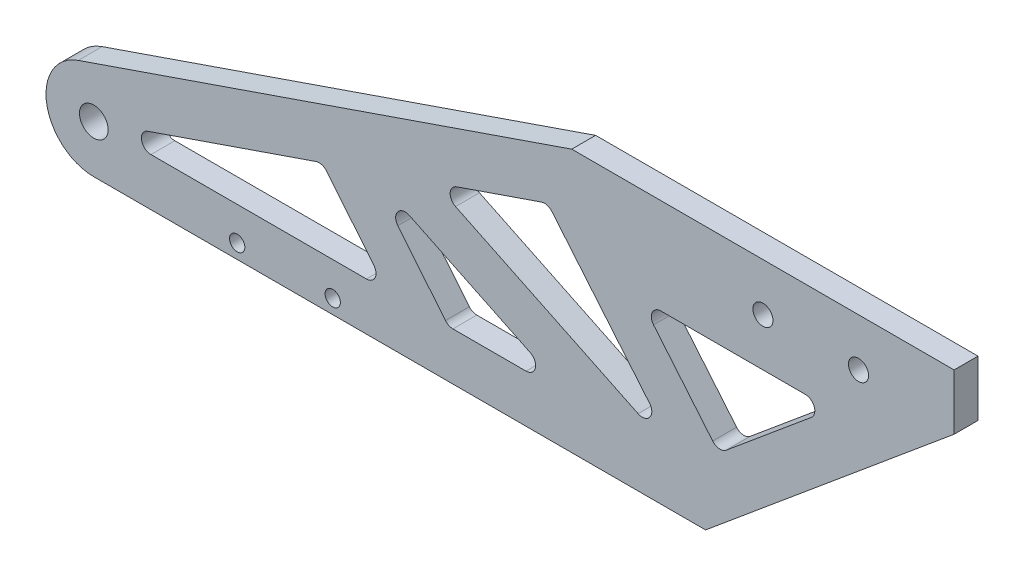
SolidWorks part; units mm, degrees
material "环氧树脂FR-4"
ref_plane "前视基准面" through (0, 0, 0) normal (0, 0, 1) x (1, 0, 0)
ref_plane "上视基准面" through (0, 0, 0) normal (0, 1, 0) x (1, 0, 0)
ref_plane "右视基准面" through (0, 0, 0) normal (1, 0, 0) x (0, 0, -1)
sketch "草图1" plane through (0, 0, 0) normal (0, 0, 1) x (1, 0, 0)
  line L0 (0, 0) -> (0, 55)
  line L1 (0, 55) -> (-80, 55)
  line L3 (-180, 0) -> (0, 0)
  line L4 (-80, 55) -> (-183.2549, 19.4554)
  arc A0 (-183.2549, 19.4554) -> (-180, 0) centre (-180, 10) ccw
  dimension "D4" = 20
  dimension "D1" = 55
  dimension "D2" = 80
  dimension "D3" = 180
  dimension "D6" = 0
extrude "凸台-拉伸1" add sketch "草图1" along normal blind 5
sketch "草图2" plane through (0, 0, 5) normal (0, 0, 1) x (1, 0, 0)
  circle A0 centre (-180, 10) radius 3
  dimension "D1" = 6
extrude "切除-拉伸1" cut sketch "草图2" against normal through all
sketch "草图3" plane through (0, 0, 5) normal (0, 0, 1) x (1, 0, 0)
  line L1 (-80, 55) -> (-183.2549, 19.4554) construction
  line L6 (-113.975, 26.0008) -> (-88.6926, 13.8013)
  line L7 (-89.5618, 10) -> (-104.8668, 10)
  line L17 (-106.415, 10.7338) -> (-116.3924, 22.9334)
  line L26 (-168.6966, 13.8911) -> (-133.51, 26.0037)
  line L30 (-131.3109, 25.3788) -> (-121.4046, 13.2662)
  line L34 (-10, 30.7299) -> (-10, 12)
  line L35 (-12, 10) -> (-34.4759, 10)
  line L36 (-35.7563, 13.5364) -> (-13.2804, 32.2664)
  line L37 (-180, 0) -> (0, 0) construction
  line L38 (0, 0) -> (0, 55) construction
  line L39 (0, 55) -> (-80, 55) construction
  line L40 (-61.3504, 35) -> (-31.1446, 35)
  line L41 (-29.8642, 31.4636) -> (-47.6906, 16.6082)
  line L42 (-50.5074, 16.8643) -> (-62.8869, 31.7196)
  line L43 (-84.1609, 41.628) -> (-63.7173, 17.0956)
  line L44 (-66.1229, 14.014) -> (-104.3075, 32.4392)
  line L45 (-104.0893, 36.1316) -> (-86.3483, 42.2387)
  line L46 (-122.9527, 10) -> (-168.0456, 10)
  arc A0 (-168.6966, 13.8911) -> (-168.0456, 10) centre (-168.0456, 12) ccw
  arc A1 (-10, 12) -> (-12, 10) centre (-12, 12) cw
  arc A2 (-10, 30.7299) -> (-13.2804, 32.2664) centre (-12, 30.7299) ccw
  arc A3 (-34.4759, 10) -> (-35.7563, 13.5364) centre (-34.4759, 12) cw
  arc A4 (-31.1446, 35) -> (-29.8642, 31.4636) centre (-31.1446, 33) cw
  arc A5 (-47.6906, 16.6082) -> (-50.5074, 16.8643) centre (-48.971, 18.1447) cw
  arc A6 (-61.3504, 35) -> (-62.8869, 31.7196) centre (-61.3504, 33) ccw
  arc A7 (-63.7173, 17.0956) -> (-66.1229, 14.014) centre (-65.2537, 15.8153) cw
  arc A8 (-84.1609, 41.628) -> (-86.3483, 42.2387) centre (-85.6974, 40.3476) ccw
  arc A9 (-104.3075, 32.4392) -> (-104.0893, 36.1316) centre (-103.4383, 34.2405) cw
  arc A10 (-88.6926, 13.8013) -> (-89.5618, 10) centre (-89.5618, 12) cw
  arc A11 (-104.8668, 10) -> (-106.415, 10.7338) centre (-104.8668, 12) cw
  arc A12 (-113.975, 26.0008) -> (-116.3924, 22.9334) centre (-114.8442, 24.1995) ccw
  arc A13 (-121.4046, 13.2662) -> (-122.9527, 10) centre (-122.9527, 12) cw
  arc A14 (-133.51, 26.0037) -> (-131.3109, 25.3788) centre (-132.859, 24.1127) cw
  point P27 (-10, 10)
  point P30 (-10, 35)
  point P33 (-40, 10)
  point P36 (-25.6205, 35)
  point P41 (-65.6205, 35)
  point P44 (-57.8042, 10)
  point P47 (-85.044, 42.6877)
  point P50 (-108.6826, 34.5504)
  point P53 (-80.8149, 10)
  point P56 (-105.8149, 10)
  point P59 (-122.1123, 29.9273)
  dimension "D17" = 10
  dimension "D18" = 10
  dimension "D19" = 2
  dimension "D20" = 2
  dimension "D1" = 10
  dimension "D2" = 10
  dimension "D3" = 20
  dimension "D4" = 30
  dimension "D5" = 20
  dimension "D6" = 10
  dimension "D7" = 40
  dimension "D8" = 10
  dimension "D9" = 10
  dimension "D10" = 0
  dimension "D11" = 25
  dimension "D12" = 10
  dimension "D13" = 10
  dimension "D14" = 10
  dimension "D15" = 25
  dimension "D16" = 10
extrude "切除-拉伸2" cut sketch "草图3" against normal through all
sketch "草图4" plane through (0, 0, 5) normal (0, 0, 1) x (1, 0, 0)
  line L0 (-180, 0) -> (0, 0) construction
  circle A0 centre (-180, 10) radius 3 construction
  point P0 (-150, 3)
  point P1 (-130, 3)
  dimension "D1" = 30
  dimension "D2" = 20
  dimension "D3" = 3
  dimension "D4" = 3
hole_wizard "Ø3.2 (3.2) 直径孔1" positions "3D草图1" profile "草图5" hole size "Ø3.2" standard "GB" end condition through all
sketch3d "3D草图1"
  point P0 (-150, 3, 5)
  point P3 (-130, 3, 5)
sketch "草图5" plane through (-150, 3, 5) normal (1, 0, 0) x (0, -1, 0)
  line L0 (0, 0) -> (0, 5)
  line L1 (0, 5) -> (1.6, 5)
  line L2 (1.6, 5) -> (1.6, 0)
  line L5 (1.6, 0) -> (0, 0)
  line L11 (0, -6.35) -> (0, 107.95) construction
  dimension "通孔孔直径" = 3.2
  dimension "通孔孔深度" = 5
sketch "草图6" plane through (0, 0, 5) normal (0, 0, 1) x (1, 0, 0)
  line L0 (0, 55) -> (-80, 55) construction
  line L1 (0, 0) -> (0, 55) construction
  point P0 (-40, 45)
  point P1 (-20, 45)
  dimension "D1" = 10
  dimension "D2" = 20
  dimension "D3" = 20
  dimension "D4" = 10
hole_wizard "Ø4.2 (4.2) 直径孔1" positions "3D草图2" profile "草图7" hole size "Ø4.2" standard "GB" end condition through all
sketch3d "3D草图2"
  point P0 (-40, 45, 5)
  point P3 (-20, 45, 5)
sketch "草图7" plane through (-40, 45, 5) normal (1, 0, 0) x (0, -1, 0)
  line L0 (0, 0) -> (0, 5)
  line L1 (0, 5) -> (2.1, 5)
  line L2 (2.1, 5) -> (2.1, 0)
  line L5 (2.1, 0) -> (0, 0)
  line L11 (0, -6.35) -> (0, 107.95) construction
  dimension "通孔孔直径" = 4.2
  dimension "通孔孔深度" = 5
sketch "草图8" plane through (0, 0, 5) normal (0, 0, 1) x (1, 0, 0)
  line L0 (0, 0) -> (0, 43.3333)
  line L1 (0, 0) -> (0, 55) construction
  line L2 (0, 43.3333) -> (-52, 0)
  line L3 (-180, 0) -> (0, 0) construction
  line L4 (-52, 0) -> (0, 0)
  line L5 (-13.2804, 32.2664) -> (-35.7563, 13.5364) construction
extrude "切除-拉伸3" cut sketch "草图8" against normal through all
